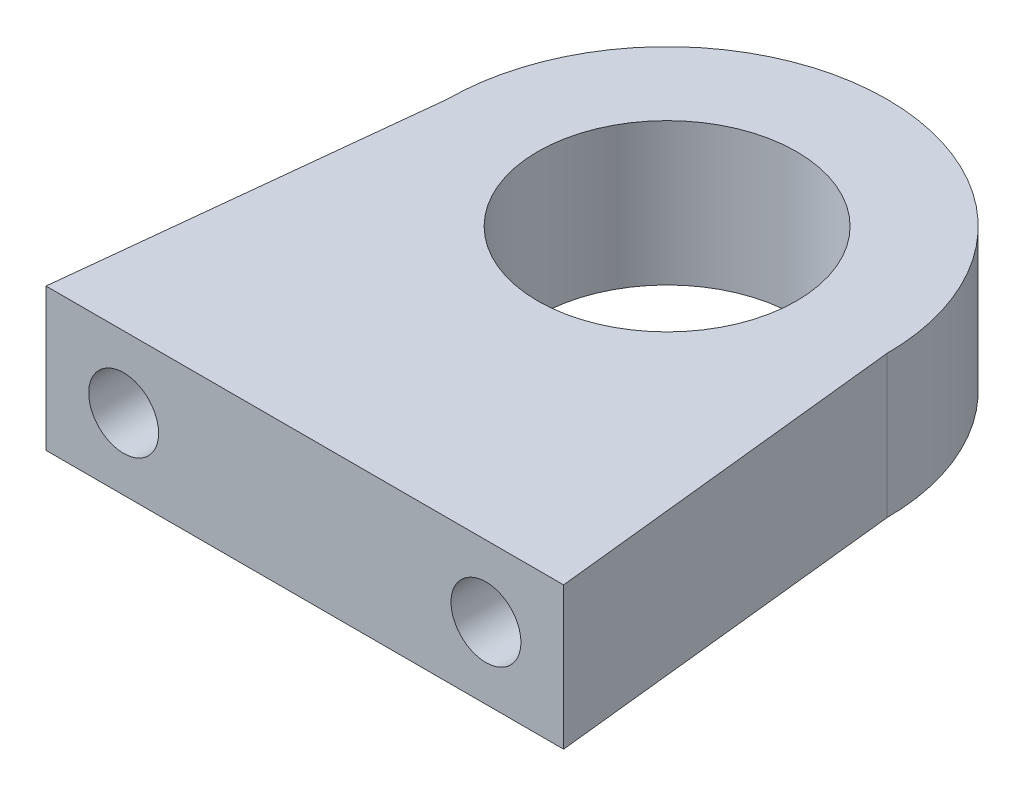
SolidWorks part; units mm, degrees
ref_plane "Front Plane" through (0, 0, 0) normal (0, 0, 1) x (1, 0, 0)
ref_plane "Top Plane" through (0, 0, 0) normal (0, 1, 0) x (1, 0, 0)
ref_plane "Right Plane" through (0, 0, 0) normal (1, 0, 0) x (0, 0, -1)
sketch "Sketch1" plane through (0, 0, 0) normal (0, 1, 0) x (1, 0, 0)
  line L0 (-10, 0) -> (-8.5, 14)
  line L1 (-10, 0) -> (10, 0)
  line L2 (10, 0) -> (8.5, 14)
  line L3 (-8.5, 14) -> (8.5, 14) construction
  line L4 (0, 14) -> (0, 0) construction
  arc A0 (-8.5, 14) -> (8.5, 14) centre (0, 14) cw
  circle A1 centre (0, 14) radius 5
  dimension "D1" = 8.5
  dimension "D3" = 14
  dimension "D4" = 10
  dimension "D2" = 20
extrude "Boss-Extrude1" add sketch "Sketch1" along normal blind 5.5
sketch "Sketch2" plane through (0, 0, 0) normal (0, 0, 1) x (1, 0, 0)
  line L0 (-10, 2.75) -> (10, 2.75) construction
  line L1 (-10, 5.5) -> (-10, 0) construction
  line L2 (10, 5.5) -> (10, 0) construction
  line L3 (0, 0) -> (0, 5.5) construction
  line L4 (-10, 0) -> (10, 0) construction
  line L5 (-10, 5.5) -> (10, 5.5) construction
  circle A0 centre (-7, 2.75) radius 1.35
  circle A2 centre (7, 2.75) radius 1.35
  dimension "D1" = 2.7
  dimension "D2" = 7
extrude "Cut-Extrude1" cut sketch "Sketch2" against normal blind 10
